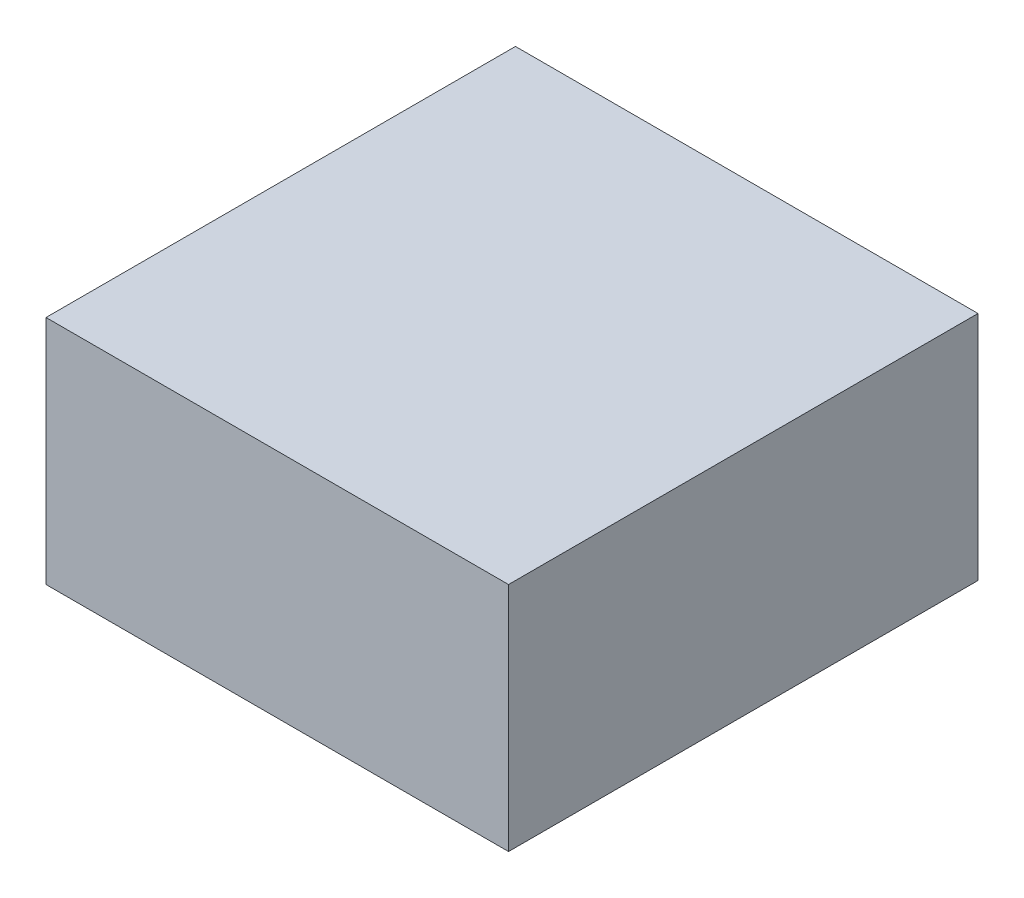
SolidWorks part; units mm, degrees
material "5052-H32"
ref_plane "Front Plane" through (0, 0, 0) normal (0, 0, 1) x (1, 0, 0)
ref_plane "Top Plane" through (0, 0, 0) normal (0, 1, 0) x (1, 0, 0)
ref_plane "Right Plane" through (0, 0, 0) normal (1, 0, 0) x (0, 0, -1)
sketch "Sketch1" plane through (0, 0, 0) normal (0, 0, 1) x (1, 0, 0)
  line L1 (-100, 50) -> (100, 50)
  line L2 (-100, 50) -> (-100, -50)
  line L3 (-100, -50) -> (100, -50)
  line L4 (100, 50) -> (100, -50)
  dimension "D1" = 200
  dimension "D2" = 100
  dimension "D3" = 50
  dimension "D4" = 100
extrude "Boss-Extrude1" add sketch "Sketch1" along normal blind 203
